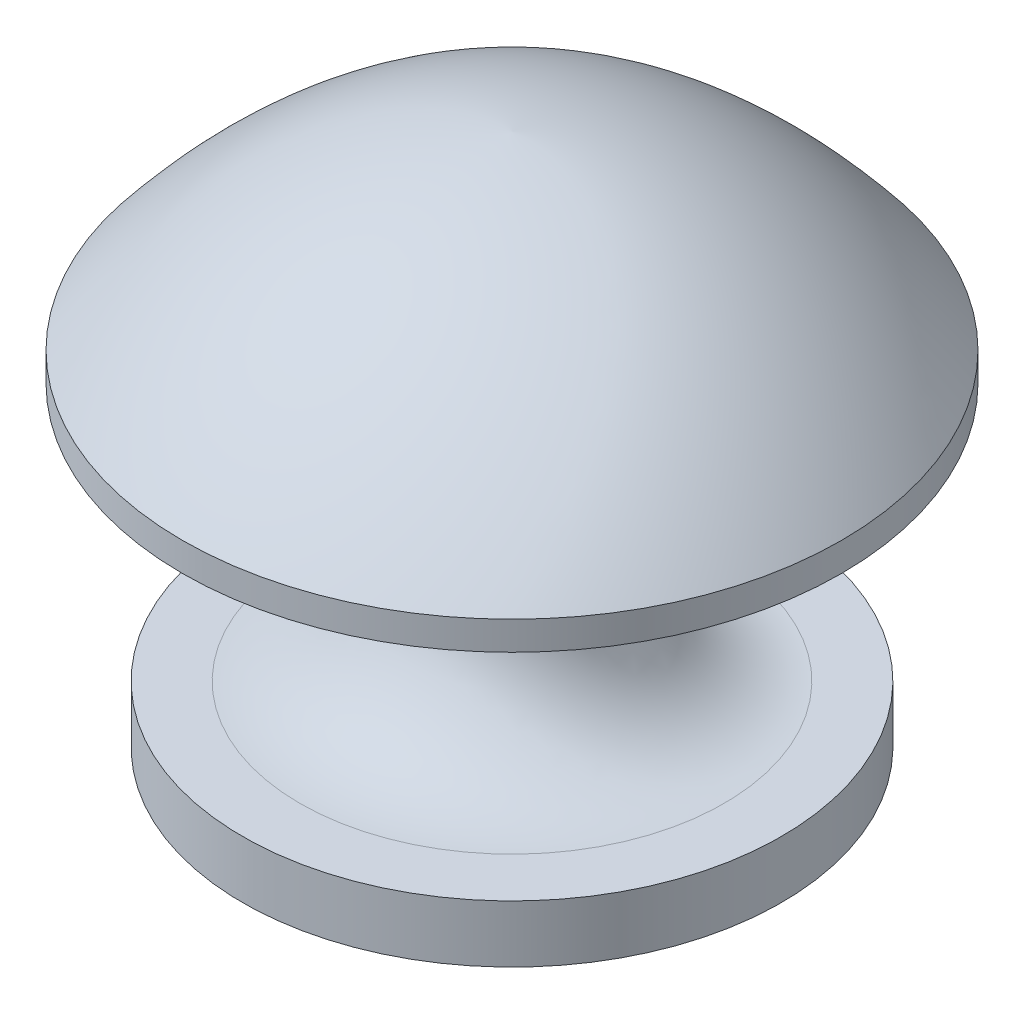
SolidWorks part; units mm, degrees
material "Maple"
ref_plane "Front Plane" through (0, 0, 0) normal (0, 0, 1) x (1, 0, 0)
ref_plane "Top Plane" through (0, 0, 0) normal (0, 1, 0) x (1, 0, 0)
ref_plane "Right Plane" through (0, 0, 0) normal (1, 0, 0) x (0, 0, -1)
sketch "Sketch1" plane through (0, 0, 0) normal (0, 0, 1) x (1, 0, 0)
  line L0 (0, 0) -> (-11.938, 0)
  line L1 (-11.938, 0) -> (-11.938, 2.54)
  line L2 (-11.938, 2.54) -> (-9.398, 2.54)
  line L4 (-9.398, 13.97) -> (-14.605, 13.97)
  line L7 (0, 0) -> (0, 23.622)
  line L8 (-14.605, 13.97) -> (-14.605, 15.24)
  arc A1 (-9.398, 2.54) -> (-9.398, 13.97) centre (-9.398, 8.255) ccw
  spline S0 degree 2 poles (-14.605, 15.24) (-8.279, 23.0942) (0, 23.622) knots 0 0 0 0.874067 0.874067 0.874067
  point P11 (-14.605, 23.622)
  dimension "D6" = 1.27
  dimension "D1" = 11.938
  dimension "D2" = 2.54
  dimension "D4" = 14.605
  dimension "D5" = 11.43
  dimension "D7" = 2.54
revolve "Revolve1" add sketch "Sketch1" angle 360 about L7
